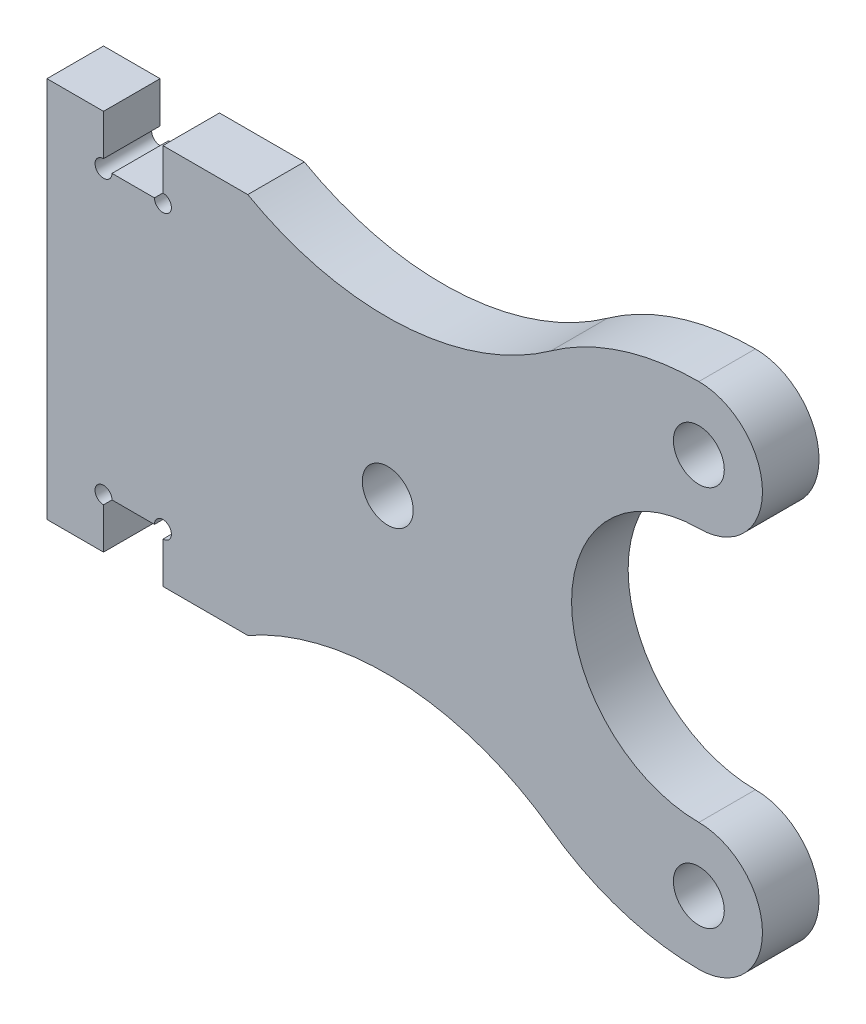
SolidWorks part; units mm, degrees
ref_plane "前视基准面" through (0, 0, 0) normal (0, 0, 1) x (1, 0, 0)
ref_plane "上视基准面" through (0, 0, 0) normal (0, 1, 0) x (1, 0, 0)
ref_plane "右视基准面" through (0, 0, 0) normal (1, 0, 0) x (0, 0, -1)
sketch "草图1" plane through (0, 0, 0) normal (0, 0, 1) x (1, 0, 0)
  line L5 (-13.95, -5.3) -> (-13.95, -6.75)
  line L6 (-15.75, -5) -> (-14.25, -5)
  line L7 (-16.05, -6.75) -> (-16.05, -5.3)
  line L8 (-18.05, -6.75) -> (-16.05, -6.75)
  line L9 (-18.05, 6.75) -> (-18.05, -6.75)
  line L10 (-16.05, 6.75) -> (-18.05, 6.75)
  line L11 (-16.05, 5.3) -> (-16.05, 6.75)
  line L12 (-14.25, 5) -> (-15.75, 5)
  line L13 (-13.95, 6.75) -> (-13.95, 5.3)
  line L14 (-10.95, 6.75) -> (-13.95, 6.75)
  line L21 (-13.95, -6.75) -> (-10.95, -6.75)
  line L23 (-18.05, 0) -> (13.9244, 0) construction
  line L24 (-15, 0) -> (-15, 5) construction
  arc A0 (-0.2302, -7.3243) -> (5, -9) centre (5, 0) ccw
  circle A1 centre (-6, 0) radius 0.9
  arc A2 (-13.95, -5.3) -> (-14.25, -5) centre (-13.95, -5) ccw
  arc A3 (-15.75, -5) -> (-16.05, -5.3) centre (-16.05, -5) ccw
  arc A4 (-16.05, 5.3) -> (-15.75, 5) centre (-16.05, 5) ccw
  arc A5 (-14.25, 5) -> (-13.95, 5.3) centre (-13.95, 5) ccw
  circle A6 centre (5, 6.75) radius 0.9
  circle A7 centre (5, -6.75) radius 0.9
  arc A8 (5, 4.5) -> (5, -4.5) centre (5, 0) ccw
  arc A10 (5, 9) -> (-0.2302, 7.3243) centre (5, 0) ccw
  arc A11 (5, 9) -> (5, 4.5) centre (5, 6.75) cw
  arc A12 (5, -4.5) -> (5, -9) centre (5, -6.75) cw
  arc A13 (-10.95, 6.75) -> (-0.2302, 7.3243) centre (-6.0415, 15.4624) ccw
  arc A14 (-0.2302, -7.3243) -> (-10.95, -6.75) centre (-6.0415, -15.4624) ccw
  point P21 (-0.9529, -6.75)
  point P26 (-0.9529, 6.75)
  point P53 (-13.95, 6.025)
  dimension "D3" = 0.3
  dimension "D6" = 20
  dimension "D7" = 9
  dimension "D8" = 10
  dimension "D12" = 3
  dimension "D13" = 11
  dimension "D14" = 1.8
  dimension "D15" = 1.8
  dimension "D1" = 10
  dimension "D2" = 13.5
  dimension "D4" = 2.1
  dimension "D5" = 2
  dimension "D10" = 15
  dimension "D11" = 13.5
extrude "凸台-拉伸1" add sketch "草图1" along normal blind 2
